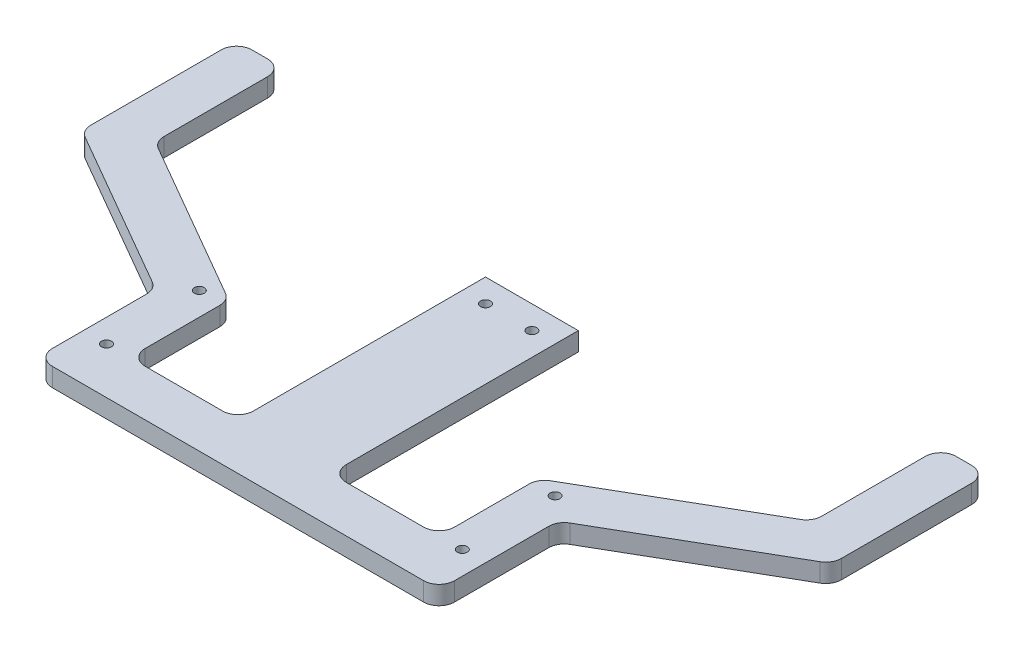
SolidWorks part; units mm, degrees
ref_plane "Front Plane" through (0, 0, 0) normal (0, 0, 1) x (1, 0, 0)
ref_plane "Top Plane" through (0, 0, 0) normal (0, 1, 0) x (1, 0, 0)
ref_plane "Right Plane" through (0, 0, 0) normal (1, 0, 0) x (0, 0, -1)
sketch "Sketch1" plane through (0, 0, 0) normal (0, 1, 0) x (1, 0, 0)
  line L1 (-50, 0) -> (-50, 32)
  line L3 (-65, 23.3397) -> (-65, -15)
  line L4 (-65, -15) -> (0, -15)
  line L5 (0, -15) -> (0, 0)
  line L6 (-15, 0) -> (-15, 80)
  line L7 (-15, 80) -> (0, 80)
  line L8 (0, 80) -> (0, 0)
  line L9 (-50, 0) -> (-15, 0)
  line L10 (-121.2917, 55.8397) -> (-65, 23.3397)
  line L12 (-106.2917, 64.5) -> (-50, 32)
  line L13 (-121.2917, 55.8397) -> (-121.2917, 105.8397)
  line L14 (-121.2917, 105.8397) -> (-106.2917, 105.8397)
  line L15 (-106.2917, 105.8397) -> (-106.2917, 64.5)
  point P11 (-65, 50)
  point P14 (0, 0)
  point P15 (-65, 23.1896)
  point P16 (-106.9595, 63.3148)
  dimension "D1" = 65
  dimension "D2" = 32
  dimension "D3" = 15
  dimension "D4" = 15
  dimension "D5" = 80
  dimension "D6" = 60
  dimension "D7" = 65
  dimension "D8" = 15
  dimension "D9" = 50
  dimension "D10" = 15
extrude "Boss-Extrude1" add sketch "Sketch1" along normal blind 6
fillet "Fillet1" radius 5 9 edges at (-65, 3, 15) (-15, 3, 0) (-50, 3, 0) (-50, 3, -32) (-65, 3, -23.3397) (-121.2917, 3, -105.8397) (-106.2917, 3, -105.8397) (-106.2917, 3, -64.5) (-121.2917, 3, -55.8397)
sketch "Sketch2" plane through (0, 6, 0) normal (0, 1, 0) x (1, 0, 0)
  line L0 (-65, 30) -> (-50, 30) construction
  line L1 (0, 80) -> (-15, 80) construction
  line L3 (-15, 72.5) -> (0, 72.5) construction
  line L4 (-15, 80) -> (-15, 5) construction
  line L5 (0, -15) -> (0, 80) construction
  line L6 (0, 72.5) -> (-7.5, 72.5) construction
  line L7 (-65, 20.453) -> (-65, -10) construction
  line L8 (-50, 5) -> (-50, 29.1132) construction
  line L9 (-20, 0) -> (-45, 0) construction
  circle A2 centre (-7.5, 72.5) radius 1.6
  circle A3 centre (-57.5, 30) radius 1.6
  circle A4 centre (-57.5, 0) radius 1.6
  point P24 (0, 0)
  point P25 (0, 0)
  dimension "D1" = 3.2
  dimension "D3" = 3.2
  dimension "D2" = 30
  dimension "D4" = 7.5
extrude "Cut-Extrude1" cut sketch "Sketch2" against normal through all
mirror "Mirror1" about plane through (0, 0, 0) normal (1, 0, 0) of "Cut-Extrude1", "Boss-Extrude1", "Fillet1"
